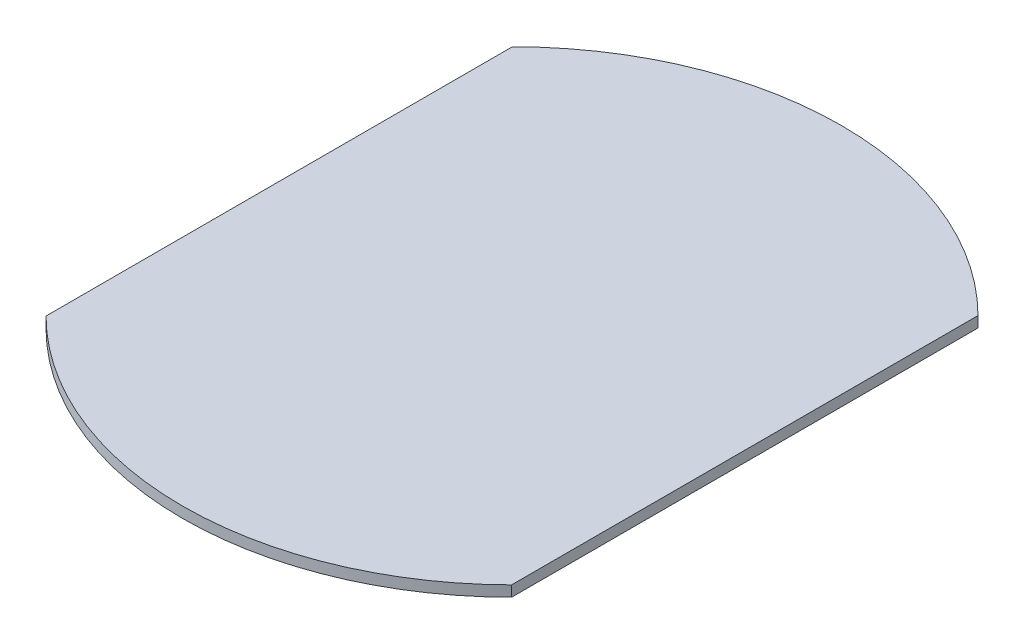
SolidWorks part; units mm, degrees
ref_plane "Спереди" through (0, 0, 0) normal (0, 0, 1) x (1, 0, 0)
ref_plane "Сверху" through (0, 0, 0) normal (0, 1, 0) x (1, 0, 0)
ref_plane "Справа" through (0, 0, 0) normal (1, 0, 0) x (0, 0, -1)
sketch "Эскиз1" plane through (0, 0, 0) normal (0, 1, 0) x (1, 0, 0)
  line L0 (-2637.887, 0) -> (129256.4613, 0) construction
  line L1 (0, -2637.887) -> (0, 129256.4613) construction
  line L2 (32.5, -32.5538) -> (32.5, 32.5538)
  line L3 (-32.5, -32.5538) -> (-32.5, 32.5538)
  arc A0 (-32.5, 32.5538) -> (32.5, 32.5538) centre (0, 0) cw
  arc A1 (-32.5, -32.5538) -> (32.5, -32.5538) centre (0, 0) ccw
  point P7 (0, -46)
  point P11 (0, 46)
  dimension "D1" = 92
  dimension "D2" = 65
extrude "Бобышка-Вытянуть1" add sketch "Эскиз1" along normal mid plane 1.5
